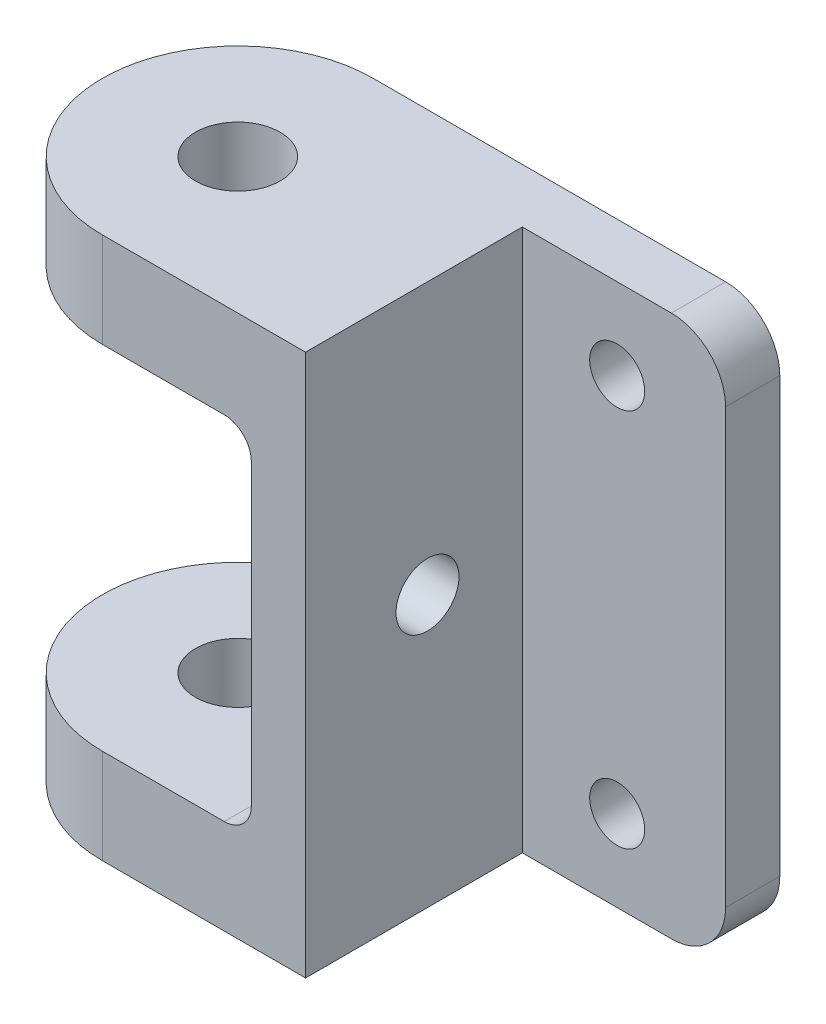
SolidWorks part; units mm, degrees
other "DetailItem1"
ref_plane "Front Plane" through (0, 0, 0) normal (0, 0, 1) x (1, 0, 0)
ref_plane "Top Plane" through (0, 0, 0) normal (0, 1, 0) x (1, 0, 0)
ref_plane "Right Plane" through (0, 0, 0) normal (1, 0, 0) x (0, 0, -1)
sketch "Sketch1" plane through (0, 0, 0) normal (0, 1, 0) x (1, 0, 0)
  line L0 (0, 0) -> (-76.2, 0)
  line L1 (-76.2, -50.8) -> (-38.1, -50.8)
  line L2 (-38.1, -10.16) -> (0, -10.16)
  line L3 (0, -10.16) -> (0, 0)
  line L4 (-38.1, -10.16) -> (-38.1, -50.8)
  arc A0 (-76.2, 0) -> (-76.2, -50.8) centre (-76.2, -25.4) ccw
  circle A1 centre (-76.2, -25.4) radius 7.9375
  dimension "D1" = 50.8
  dimension "D3" = 15.875
  dimension "D2" = 10.16
  dimension "D4" = 38.1
  dimension "D5" = 38.1
extrude "Boss-Extrude1" add sketch "Sketch1" against normal blind 101.6
sketch "Sketch2" plane through (0, 0, 50.8) normal (0, 0, 1) x (1, 0, 0)
  line L0 (-76.2, 0) -> (-101.6, 0) construction
  line L1 (-53.34, -17.78) -> (-111.0299, -17.78)
  line L2 (-48.26, -22.86) -> (-48.26, -78.74)
  line L3 (-53.34, -83.82) -> (-111.0299, -83.82)
  line L4 (-111.0299, -17.78) -> (-111.0299, -83.82)
  line L5 (-101.6, -101.6) -> (-76.2, -101.6) construction
  line L6 (-38.1, -101.6) -> (-38.1, 0) construction
  arc A0 (-48.26, -22.86) -> (-53.34, -17.78) centre (-53.34, -22.86) ccw
  arc A1 (-53.34, -83.82) -> (-48.26, -78.74) centre (-53.34, -78.74) ccw
  dimension "D4" = 5.08
  dimension "D5" = 5.08
  dimension "D1" = 17.78
  dimension "D2" = 17.78
  dimension "D3" = 10.16
extrude "Cut-Extrude1" cut sketch "Sketch2" against normal through all
sketch "Sketch3" plane through (0, 0, 10.16) normal (0, 0, 1) x (1, 0, 0)
  line L0 (-38.1, 0) -> (0, 0) construction
  line L1 (-38.1, -101.6) -> (-38.1, 0) construction
  circle A0 centre (-20.32, -15.24) radius 5.1562
  circle A1 centre (-20.32, -86.36) radius 5.1562
  dimension "D1" = 15.24
  dimension "D2" = 17.78
  dimension "D3" = 10.3124
  dimension "D4" = 2
extrude "Cut-Extrude2" cut sketch "Sketch3" against normal through all
sketch "Sketch4" plane through (-38.1, 0, 0) normal (1, 0, 0) x (0, 0, -1)
  line L0 (-50.8, 0) -> (-10.16, 0) construction
  line L1 (-10.16, -101.6) -> (-10.16, 0) construction
  circle A0 centre (-27.94, -50.8) radius 5.9034
  dimension "D1" = 50.8
  dimension "D2" = 17.78
extrude "Cut-Extrude3" cut sketch "Sketch4" against normal through all
fillet "Fillet1" radius 10.16 2 edges at (0, 0, 5.08) (0, -101.6, 5.08)
